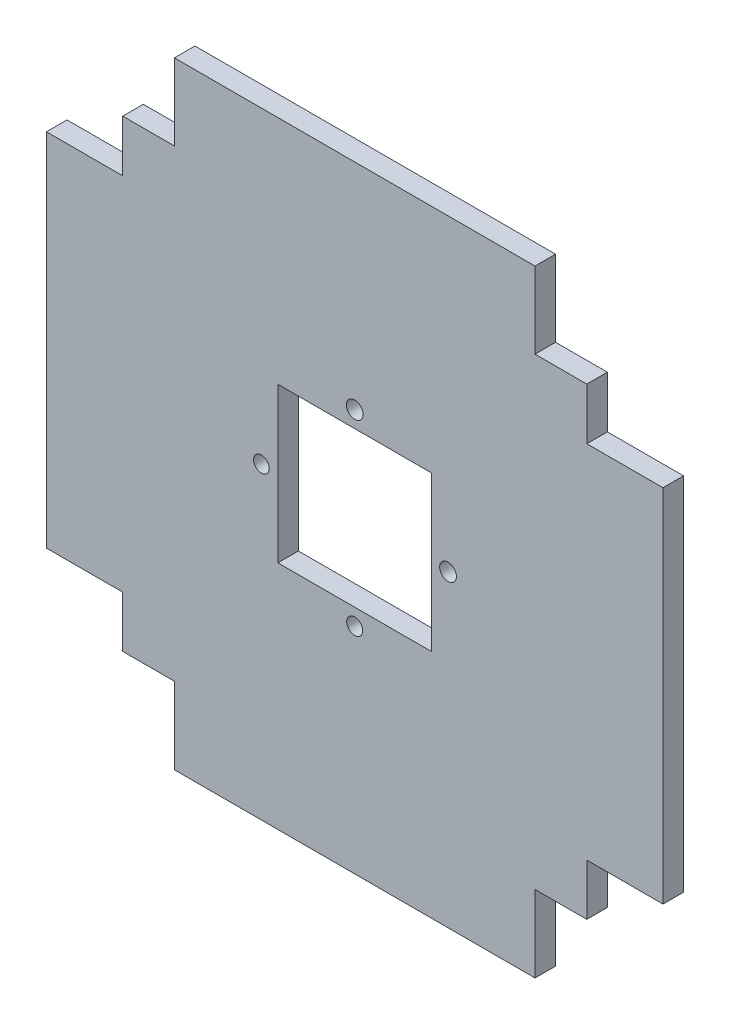
SolidWorks part; units mm, degrees
ref_plane "Front Plane" through (0, 0, 0) normal (0, 0, 1) x (1, 0, 0)
ref_plane "Top Plane" through (0, 0, 0) normal (0, 1, 0) x (1, 0, 0)
ref_plane "Right Plane" through (0, 0, 0) normal (1, 0, 0) x (0, 0, -1)
sketch "Sketch1" plane through (0, 0, 0) normal (0, 0, 1) x (1, 0, 0)
  line L1 (-46.5413, 64.7928) -> (42.5868, 64.7928)
  line L2 (-78.1772, 33.1569) -> (-78.1772, -55.9713)
  line L3 (-46.5413, -87.6072) -> (42.5868, -87.6072)
  line L4 (74.2228, 33.1569) -> (74.2228, -55.9713)
  line L5 (-20.9744, 7.7058) -> (17.0199, 7.7058)
  line L6 (-20.9744, 7.7058) -> (-20.9744, -30.5202)
  line L7 (-78.1772, 33.1569) -> (-59.3174, 33.1569)
  line L8 (-46.5413, 64.7928) -> (-46.5413, 45.9329)
  line L9 (-46.5413, 45.9329) -> (-59.3174, 45.9329)
  line L10 (-59.3174, 33.1569) -> (-59.3174, 45.9329)
  line L11 (-78.1772, -55.9713) -> (-59.3174, -55.9713)
  line L12 (-46.5413, -87.6072) -> (-46.5413, -68.6523)
  line L13 (-20.9744, -30.5202) -> (17.0199, -30.5202)
  line L14 (17.0199, 7.7058) -> (17.0199, -30.5202)
  line L15 (74.2228, -55.9713) -> (55.389, -55.9713)
  line L16 (42.5868, -87.6072) -> (42.5868, -68.6523)
  line L17 (-46.5413, -68.6523) -> (-59.3174, -68.6523)
  line L18 (-59.3174, -55.9713) -> (-59.3174, -68.6523)
  line L19 (74.2228, 33.1569) -> (55.389, 33.1569)
  line L20 (42.5868, 64.7928) -> (42.5868, 45.9329)
  line L23 (42.5868, -68.6523) -> (55.389, -68.6523)
  line L24 (55.389, -55.9713) -> (55.389, -68.6523)
  line L27 (42.5868, 45.9329) -> (55.389, 45.9329)
  line L28 (55.389, 33.1569) -> (55.389, 45.9329)
  circle A0 centre (-25.0384, -11.4072) radius 1.9321
  circle A1 centre (-1.9772, 11.7698) radius 2.0778
  circle A2 centre (21.0839, -11.4072) radius 2.0748
  circle A3 centre (-1.9772, -34.5842) radius 1.9772
  point P4 (-1.9772, -11.4072)
extrude "Boss-Extrude1" add sketch "Sketch1" along normal blind 5.08
